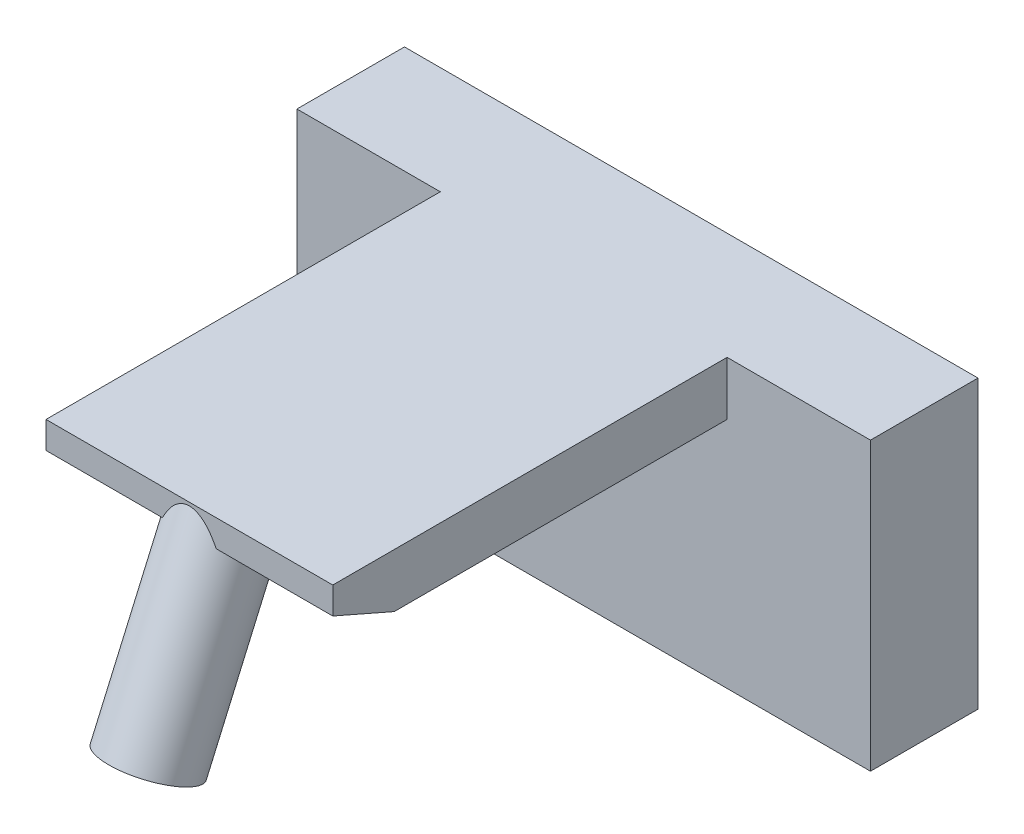
SolidWorks part; units mm, degrees
ref_plane "Front Plane" through (0, 0, 0) normal (0, 0, 1) x (1, 0, 0)
ref_plane "Top Plane" through (0, 0, 0) normal (0, 1, 0) x (1, 0, 0)
ref_plane "Right Plane" through (0, 0, 0) normal (1, 0, 0) x (0, 0, -1)
sketch "Sketch1" plane through (0, 0, 0) normal (0, 0, 1) x (1, 0, 0)
  line L1 (-21.5695, 14.0448) -> (-5.5695, 14.0448)
  line L2 (-21.5695, 14.0448) -> (-21.5695, 22.0448)
  line L3 (-21.5695, 22.0448) -> (-5.5695, 22.0448)
  line L4 (-5.5695, 14.0448) -> (-5.5695, 22.0448)
  line L5 (-21.5695, 14.0448) -> (-5.5695, 22.0448) construction
  line L6 (-21.5695, 22.0448) -> (-5.5695, 14.0448) construction
  dimension "D1" = 16
  dimension "D2" = 8
extrude "Boss-Extrude1" add sketch "Sketch1" along normal blind 3
shell "Shell3" thickness 1
sketch "Sketch2" plane through (0, 0, 2) normal (0, 0, -1) x (-1, 0, 0)
  line L0 (21.5695, 22.0448) -> (21.5695, 14.0448) construction
  line L1 (5.5695, 22.0448) -> (21.5695, 22.0448) construction
  circle A0 centre (13.5695, 18.0448) radius 1.5
  circle A1 centre (13.5695, 18.0448) radius 0.8
  point P4 (21.5695, 18.0448)
  point P7 (13.5695, 22.0448)
  dimension "D1" = 3
  dimension "D2" = 8
  dimension "D3" = 4
  dimension "D4" = 0.7
extrude "Boss-Extrude2" add sketch "Sketch2" along normal blind 2
sketch "Sketch3" plane through (0, 0, 3) normal (0, 0, 1) x (1, 0, 0)
  line L0 (-5.5695, 22.0448) -> (-21.5695, 22.0448) construction
  line L1 (-17.5695, 22.0448) -> (-9.5695, 22.0448)
  line L2 (-9.5695, 22.0448) -> (-9.5695, 20.5448)
  line L3 (-9.5695, 20.5448) -> (-11.5695, 20.5448)
  line L4 (-13.5695, 22.0448) -> (-13.5695, 14.0448) construction
  line L5 (-21.5695, 14.0448) -> (-5.5695, 14.0448) construction
  line L6 (-13.5695, 20.5448) -> (-13.6847, 20.5448)
  line L7 (-17.5695, 20.5448) -> (-15.5695, 20.5448)
  line L8 (-17.5695, 22.0448) -> (-17.5695, 20.5448)
  arc A0 (-15.5695, 20.5448) -> (-11.5695, 20.5448) centre (-13.5695, 22.0448) ccw
  dimension "D1" = 5
  dimension "D2" = 4
  dimension "D3" = 1.5
extrude "Boss-Extrude3" add sketch "Sketch3" along normal blind 11
sketch "Sketch4" plane through (-17.5695, 0, 0) normal (-1, 0, 0) x (0, 0, 1)
  line L0 (14, 21.2948) -> (14, 19.5448)
  line L1 (14, 22.0448) -> (14, 20.5448) construction
  line L2 (14, 21.2948) -> (10, 19.5448)
  line L3 (3, 19.5448) -> (14, 19.5448) construction
  line L4 (10, 19.5448) -> (14, 19.5448)
  dimension "D1" = 4
extrude "Cut-Extrude2" cut sketch "Sketch4" against normal blind 10
sketch "Sketch5" plane through (0, 12.7327, -5.5705) normal (0, -0.9162, 0.4008) x (-1, 0, 0)
  line L0 (17.5695, -20.426) -> (8.8993, -20.426) construction
  line L1 (17.5695, -21.3615) -> (17.5695, -19.4904) construction
  line L2 (13.5695, -21.3615) -> (13.5695, -16.9955) construction
  line L3 (9.5695, -21.3615) -> (17.5695, -21.3615) construction
  circle A0 centre (13.5695, -20.426) radius 1.2
  ellipse E0 centre (13.5695, -23.2327) end of major axis (13.5695, -16.9955) minor radius 2.5 (15.5695, -19.4904) -> (11.5695, -19.4904) ccw construction
  dimension "D1" = 2.4
extrude "Boss-Extrude4" add sketch "Sketch5" along normal blind 5 and the other way up to next
